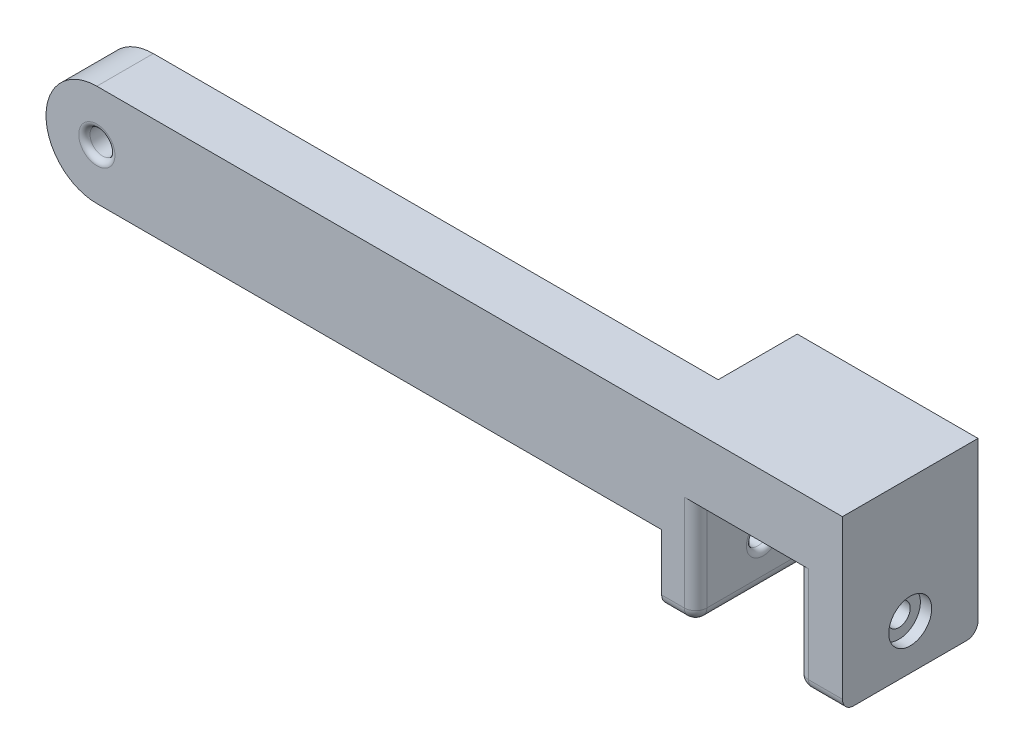
SolidWorks part; units mm, degrees
ref_plane "Front Plane" through (0, 0, 0) normal (0, 0, 1) x (1, 0, 0)
ref_plane "Top Plane" through (0, 0, 0) normal (0, 1, 0) x (1, 0, 0)
ref_plane "Right Plane" through (0, 0, 0) normal (1, 0, 0) x (0, 0, -1)
sketch "Sketch1" plane through (0, 0, 0) normal (0, 0, 1) x (1, 0, 0)
  line L0 (0, 0) -> (50, 0) construction
  line L1 (0, 4.5) -> (50, 4.5)
  line L2 (0, -4.5) -> (50, -4.5)
  line L3 (50, 4.5) -> (50, -4.5)
  circle A0 centre (0, 0) radius 1.1
  circle A2 centre (0, 0) radius 4.5
  dimension "D2" = 9
  dimension "D1" = 50
extrude "Boss-Extrude1" add sketch "Sketch1" along normal blind 5
sketch "Sketch2" plane through (0, 4.5, 0) normal (0, 1, 0) x (1, 0, 0)
  line L0 (50, -5) -> (50, 0) construction
  line L2 (0, 0) -> (50, 0) construction
  line L3 (50, 7) -> (66, 7)
  line L4 (50, 7) -> (50, -5)
  line L5 (50, -5) -> (66, -5)
  line L6 (66, 7) -> (66, -5)
  line L7 (50, 7) -> (66, -5) construction
  line L8 (50, -5) -> (66, 7) construction
  point P4 (58, 1)
  dimension "D1" = 12
  dimension "D2" = 0
  dimension "D3" = 1
  dimension "D4" = 16
extrude "Boss-Extrude2" add sketch "Sketch2" against normal blind 15
sketch "Sketch3" plane through (0, 4.5, 0) normal (0, 1, 0) x (1, 0, 0)
  line L0 (0, -5) -> (66, -5) construction
  line L1 (53, 9) -> (62, 9)
  line L2 (53, 9) -> (53, -5)
  line L3 (53, -5) -> (62, -5)
  line L4 (62, 9) -> (62, -5)
  line L5 (53, 9) -> (62, -5) construction
  line L6 (53, -5) -> (62, 9) construction
  line L7 (50, 7) -> (50, 0) construction
  line L8 (66, 7) -> (50, 7) construction
  point P0 (57.5, 2)
  dimension "D1" = 9
  dimension "D2" = 3
  dimension "D3" = 5
extrude "Cut-Extrude1" cut sketch "Sketch3" against normal blind 9.5 from offset 5.5 offset against normal yes
sketch "Sketch4" plane through (66, 0, 0) normal (1, 0, 0) x (0, 0, -1)
  line L0 (-5, -10.5) -> (7, -10.5) construction
  line L2 (7, -10.5) -> (7, 4.5) construction
  circle A0 centre (1, -6.5) radius 1
  dimension "D1" = 4
  dimension "D2" = 6
extrude "Cut-Extrude2" cut sketch "Sketch4" against normal blind 16
fillet "Fillet2" radius 0.5 1 edges at (53, -6.5, 0)
sketch "Sketch5" plane through (66, 0, 0) normal (1, 0, 0) x (0, 0, -1)
  circle A0 centre (1, -6.5) radius 1.9
extrude "Cut-Extrude3" cut sketch "Sketch5" against normal blind 1 contours A0
fillet "Fillet3" radius 1 10 edges at (53, -10.5, -1) (51.5, -10.5, 5) (53, -5.75, 5) (53, -5.75, -7) (51.5, -10.5, -7) (64, -10.5, 5) (62, -5.75, -7) (62, -5.75, 5) (64, -10.5, -7) (62, -10.5, -1)
sketch "Sketch6" plane through (50, 0, 0) normal (-1, 0, 0) x (0, 0, 1)
  circle A0 centre (-1, -6.5) radius 2
extrude "Cut-Extrude4" cut sketch "Sketch6" along normal blind 5.5 from offset 0.5 offset against normal yes
fillet "Fillet4" radius 0.5 2 edges at (1.1, 0, 5) (1.1, 0, 0)
